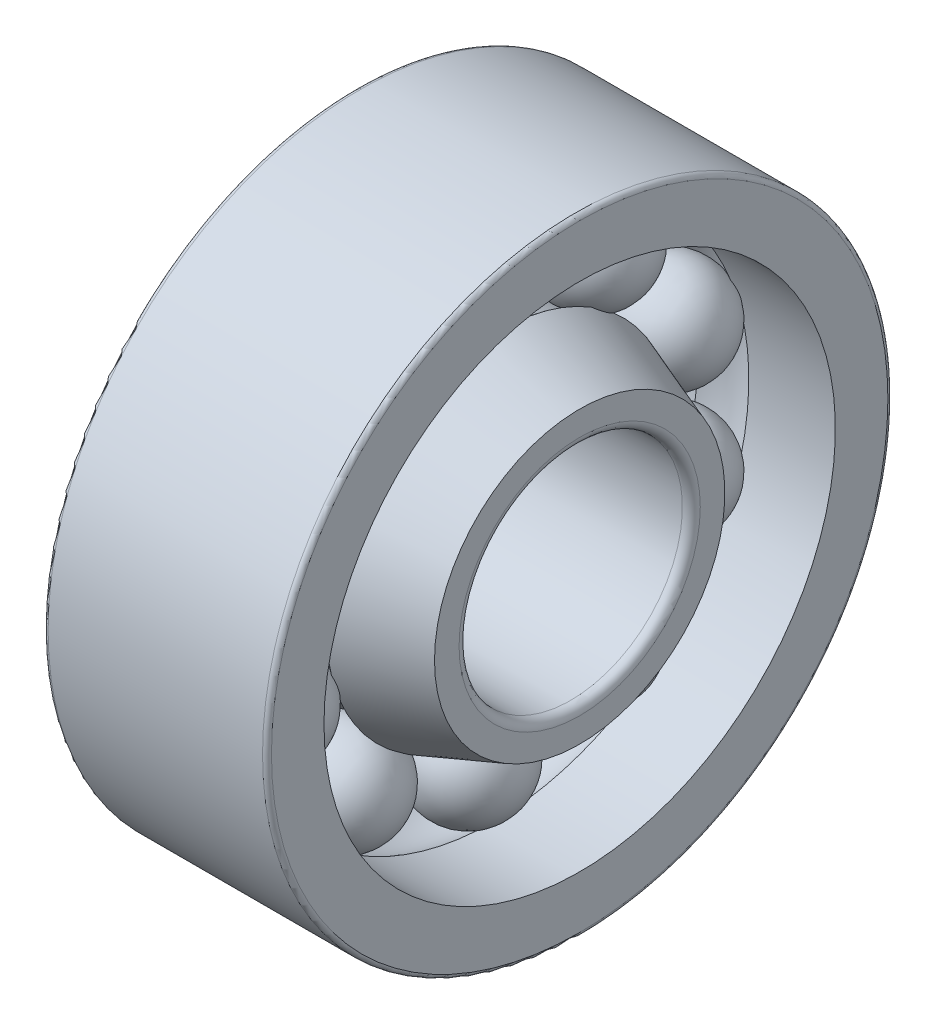
SolidWorks part; units mm, degrees
ref_plane "前视" through (0, 0, 0) normal (0, 0, 1) x (1, 0, 0)
ref_plane "上视" through (0, 0, 0) normal (0, 1, 0) x (1, 0, 0)
ref_plane "右视" through (0, 0, 0) normal (1, 0, 0) x (0, 0, -1)
sketch "尺寸草图" plane through (0, 0, 0) normal (0, 0, 1) x (1, 0, 0)
  line L0 (-3.205, -4.1476) -> (10.795, -4.1476)
  point P2 (1.795, -4.1476)
  point P3 (-3.205, -4.1476)
  point P4 (0.7517, -4.1476)
  point P7 (10.695, -4.1476)
  point P8 (10.595, -4.1476)
  dimension "DD" = 14
  dimension "d" = 5
  dimension "B" = 5
  dimension "r1" = 0.1
  dimension "r" = 0.2
sketch "草图1" plane through (0, 0, 0) normal (0, 0, 1) x (1, 0, 0)
  line L0 (0, 0) -> (106.1418, 0) construction
  line L1 (0, 0) -> (0, 122.9209) construction
  line L2 (0, 7) -> (5, 7)
  line L3 (0, 2.5) -> (5, 2.5)
  line L4 (0, 7) -> (0, 2.5)
  line L5 (5, 7) -> (5, 3.7757)
  line L6 (5, 2.5) -> (5, 3.7757)
  line L7 (5, 3.7757) -> (0, 3.7757)
  line L9 (0, 4.75) -> (95.9613, 4.75) construction
  line L10 (2.5, 0) -> (2.5, 122.9209) construction
  line L11 (2.5, 5.875) -> (4, 5.875)
  line L12 (1.9375, 5.7243) -> (0, 5.7243)
  line L13 (4, 5.875) -> (4, 6.25)
  line L14 (4, 6.25) -> (5, 6.25)
  line L15 (2.5, 4.75) -> (1.9375, 5.7243) construction
  circle A0 centre (2.5, 4.75) radius 1.125
  dimension "D3" = 30
  dimension "D1" = 5
  dimension "D2" = 2.5
  dimension "D4" = 5
  dimension "D5" = 14
  dimension "D6" = 5
  dimension "D8" = 1.125
  dimension "D9" = 1.5
  dimension "D10" = 1
sketch "草图2" plane through (0, 0, 0) normal (0, 0, 1) x (1, 0, 0)
  line L0 (4, 5.875) -> (4, 6.25) construction
  line L1 (4, 6.25) -> (5, 6.25) construction
  line L2 (0, 7) -> (5, 7) construction
  line L3 (2.5, 5.875) -> (4, 5.875) construction
  line L4 (1.9375, 5.7243) -> (0, 5.7243) construction
  line L5 (0, 0) -> (106.1418, 0) construction
  line L6 (4, 5.875) -> (4, 6.25) construction
  line L7 (4, 6.25) -> (5, 6.25) construction
  line L8 (0, 7) -> (5, 7) construction
  line L9 (2.5, 5.875) -> (4, 5.875) construction
  line L10 (1.9375, 5.7243) -> (0, 5.7243) construction
  line L11 (0, 0) -> (106.1418, 0) construction
  line L12 (5, 7) -> (5, 3.7757) construction
  line L13 (0, 7) -> (0, 2.5) construction
  line L14 (5, 7) -> (5, 6.25) construction
  line L15 (0, 7) -> (0, 5.7243) construction
  line L16 (5, 6.25) -> (2.5, 5.875) construction
  line L17 (0, 4.75) -> (95.9613, 4.75) construction
  line L18 (0, 4.75) -> (95.9613, 4.75) construction
  line L19 (5, 3.25) -> (3.2302, 3.8942)
  line L20 (5, 2.5) -> (5, 3.25)
  line L21 (1.7698, 3.8942) -> (0, 3.8942)
  line L22 (0, 2.5) -> (0, 3.8942)
  line L23 (0, 2.5) -> (5, 2.5)
  circle A0 centre (2.5, 4.75) radius 1.125 construction
  arc A1 (2.5, 5.875) -> (1.9375, 5.7243) centre (2.5, 4.75) ccw construction
  arc A3 (1.7698, 3.8942) -> (3.2302, 3.8942) centre (2.5, 4.75) ccw
  dimension "D1" = 70
revolve "基体-旋转" add sketch "草图2" angle 360 about L11
sketch "草图3" plane through (0, 0, 0) normal (0, 0, 1) x (1, 0, 0)
  line L0 (0, 4.75) -> (95.9613, 4.75) construction
  line L1 (0, 4.75) -> (95.9613, 4.75) construction
  line L2 (3.675, 4.75) -> (1.325, 4.75)
  arc A0 (3.675, 4.75) -> (1.325, 4.75) centre (2.5, 4.75) ccw
  circle A1 centre (2.5, 4.75) radius 1.125
  arc A2 (3.625, 4.75) -> (1.375, 4.75) centre (2.5, 4.75) ccw construction
  dimension "D1" = 0
  dimension "D2" = 0.05
revolve "凸台-旋转1" add sketch "草图3" angle 360 about L1
sketch "草图4" plane through (0, 0, 0) normal (0, 0, 1) x (1, 0, 0)
  line L0 (5, 2.5) -> (5, 3.7757) construction
  line L1 (0, 7) -> (0, 2.5) construction
  line L2 (0, 2.5) -> (5, 2.5) construction
  line L3 (5, 3.7757) -> (0, 3.7757) construction
  line L4 (5, 2.5) -> (5, 3.7757) construction
  line L5 (1.9375, 3.7757) -> (0, 3.7757) construction
  line L6 (0, 2.5) -> (5, 2.5) construction
  line L7 (5, 3.7757) -> (3.0625, 3.7757) construction
  line L8 (0, 0) -> (106.1418, 0) construction
  line L9 (0, 0) -> (106.1418, 0) construction
  line L10 (0, 4.75) -> (95.9613, 4.75) construction
  line L11 (0, 3.7757) -> (0, 2.5) construction
  line L12 (0, 4.75) -> (95.9613, 4.75) construction
  line L13 (0, 5.7243) -> (0, 7)
  line L14 (5, 5.7243) -> (3.0625, 5.7243)
  line L15 (0, 7) -> (5, 7)
  line L16 (1.9375, 5.7243) -> (0, 5.7243)
  line L17 (5, 7) -> (5, 5.7243)
  circle A0 centre (2.5, 4.75) radius 1.125 construction
  arc A1 (1.9375, 3.7757) -> (3.0625, 3.7757) centre (2.5, 4.75) ccw construction
  arc A2 (1.9375, 5.7243) -> (3.0625, 5.7243) centre (2.5, 4.75) cw
revolve "凸台-旋转2" add sketch "草图4" angle 360 about L9
pattern_circular "阵列(圆周)1" count 10 over 360 about axis through (0, 0, 0) along (1, 0, 0) of "凸台-旋转1"
fillet "圆角1" radius 0.1 4 edges at (5, 0, 7) (0, 0, 7) (0, 0, 2.5) (0, 0, 3.8942)
fillet "圆角2" radius 0.2 1 edges at (5, 0, 2.5)
